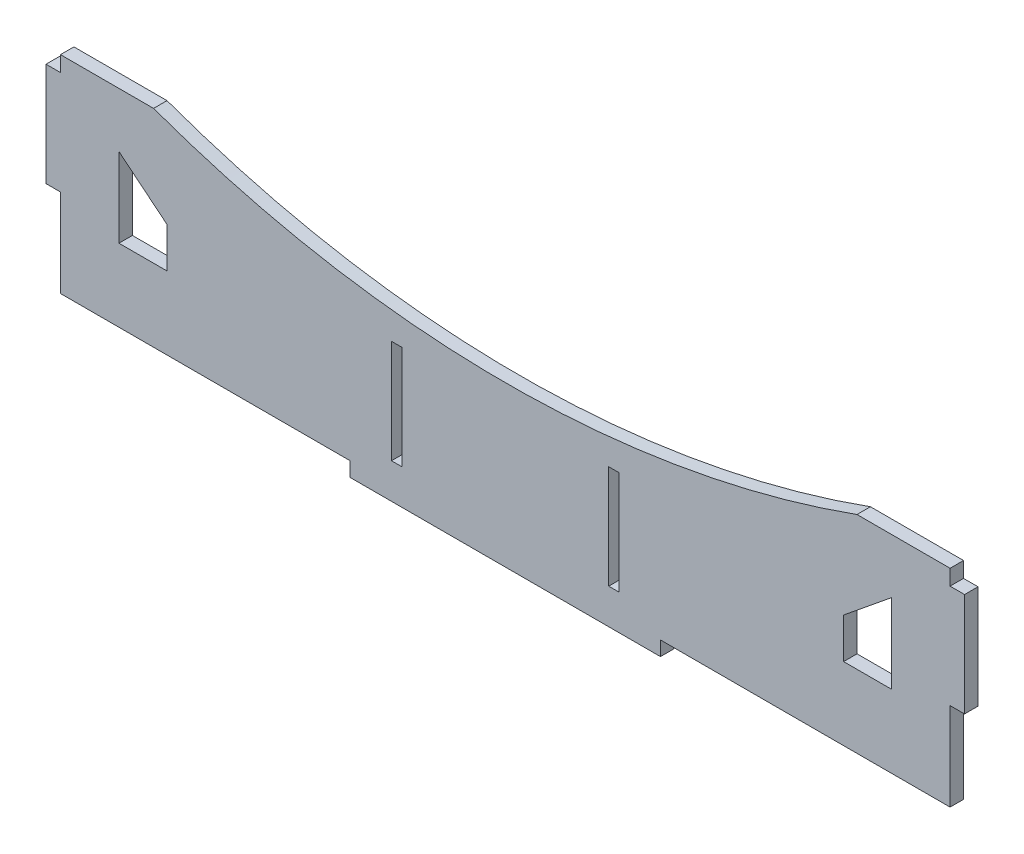
SolidWorks part; units mm, degrees
ref_plane "Front Plane" through (0, 0, 0) normal (0, 0, 1) x (1, 0, 0)
ref_plane "Top Plane" through (0, 0, 0) normal (0, 1, 0) x (1, 0, 0)
ref_plane "Right Plane" through (0, 0, 0) normal (1, 0, 0) x (0, 0, -1)
sketch "Sketch1" plane through (0, 0, 0) normal (0, 0, 1) x (1, 0, 0)
  line L1 (-43, 10) -> (43, 10)
  line L2 (-43, 10) -> (-43, -10)
  line L3 (-43, -10) -> (43, -10)
  line L4 (43, 10) -> (43, -10)
  line L5 (-43, 10) -> (43, -10) construction
  line L6 (-43, -10) -> (43, 10) construction
  point P0 (0, 0)
  dimension "D1" = 20
  dimension "D2" = 86
extrude "Boss-Extrude1" add sketch "Sketch1" along normal blind 1.3
sketch "Sketch2" plane through (0, 0, 1.3) normal (0, 0, 1) x (1, 0, 0)
  line L0 (-43, -10) -> (43, -10) construction
  line L1 (-15, -10) -> (15, -10)
  line L2 (-15, -10) -> (-15, -11.4)
  line L3 (-15, -11.4) -> (15, -11.4)
  line L4 (15, -10) -> (15, -11.4)
  line L5 (-43, 10) -> (-43, -10) construction
  line L6 (-43, 8.5) -> (-44.4, 8.5)
  line L7 (-43, 8.5) -> (-43, -1.5)
  line L8 (-43, -1.5) -> (-44.4, -1.5)
  line L9 (-44.4, 8.5) -> (-44.4, -1.5)
  line L10 (43, -10) -> (43, 10) construction
  line L11 (43, 8.5) -> (44.4, 8.5)
  line L12 (43, 8.5) -> (43, -1.5)
  line L13 (43, -1.5) -> (44.4, -1.5)
  line L14 (44.4, 8.5) -> (44.4, -1.5)
  line L15 (0, -0.715) -> (0, 0.715) construction
  dimension "D1" = 1.4
  dimension "D2" = 10
  dimension "D3" = 8.5
  dimension "D4" = 1.4
  dimension "D5" = 10
  dimension "D6" = 8.5
  dimension "D7" = 1.4
  dimension "D8" = 30
  dimension "D9" = 15
extrude "Boss-Extrude2" add sketch "Sketch2" against normal blind 1.3
sketch "Sketch3" plane through (0, 0, 1.3) normal (0, 0, 1) x (1, 0, 0)
  line L0 (0, 0) -> (0, 21.9568) construction
  line L1 (0, -0.715) -> (0, 0.715) construction
  line L2 (43, 10) -> (-43, 10) construction
  line L3 (-34, 10) -> (34, 10)
  arc A0 (-34, 10) -> (34, 10) centre (0, 103.8965) ccw
  dimension "D1" = 34
  dimension "D2" = 34
extrude "Cut-Extrude1" cut sketch "Sketch3" against normal through all contours L3 A0
sketch "Sketch4" plane through (0, 0, 1.3) normal (0, 0, 1) x (1, 0, 0)
  line L0 (0, -0.715) -> (0, 0.715) construction
  line L1 (-11, -8) -> (-10, -8)
  line L2 (-11, -8) -> (-11, 2)
  line L3 (-11, 2) -> (-10, 2)
  line L4 (-10, -8) -> (-10, 2)
  line L5 (-11, -8) -> (-10, 2) construction
  line L6 (-11, 2) -> (-10, -8) construction
  line L7 (10, -8) -> (11, -8)
  line L8 (10, -8) -> (10, 2)
  line L9 (10, 2) -> (11, 2)
  line L10 (11, -8) -> (11, 2)
  line L11 (10, -8) -> (11, 2) construction
  line L12 (10, 2) -> (11, -8) construction
  line L14 (-43, -10) -> (-15, -10) construction
  line L15 (15, -10) -> (43, -10) construction
  point P0 (-10.5, -3)
  point P5 (10.5, -3)
  dimension "D1" = 10
  dimension "D2" = 1
  dimension "D3" = 10
  dimension "D4" = 2
  dimension "D5" = 1
  dimension "D6" = 10
  dimension "D7" = 10
  dimension "D8" = 2
extrude "Cut-Extrude2" cut sketch "Sketch4" against normal through all
sketch "Sketch5" plane through (0, 0, 1.3) normal (0, 0, 1) x (1, 0, 0)
  line L0 (-37.3473, 4.7148) -> (-37.3473, -2.9619)
  line L1 (-37.3473, -2.9619) -> (-32.7085, -2.9619)
  line L2 (-32.7085, -2.9619) -> (-32.7085, 0.9381)
  line L3 (-32.7085, 0.9381) -> (-37.3473, 4.7148)
  line L4 (0, -0.715) -> (0, 0.715) construction
  line L5 (32.7085, -2.9619) -> (32.7085, 0.9381)
  line L6 (37.3473, -2.9619) -> (32.7085, -2.9619)
  line L7 (37.3473, 4.7148) -> (37.3473, -2.9619)
  line L8 (32.7085, 0.9381) -> (37.3473, 4.7148)
extrude "Cut-Extrude3" cut sketch "Sketch5" against normal through all
